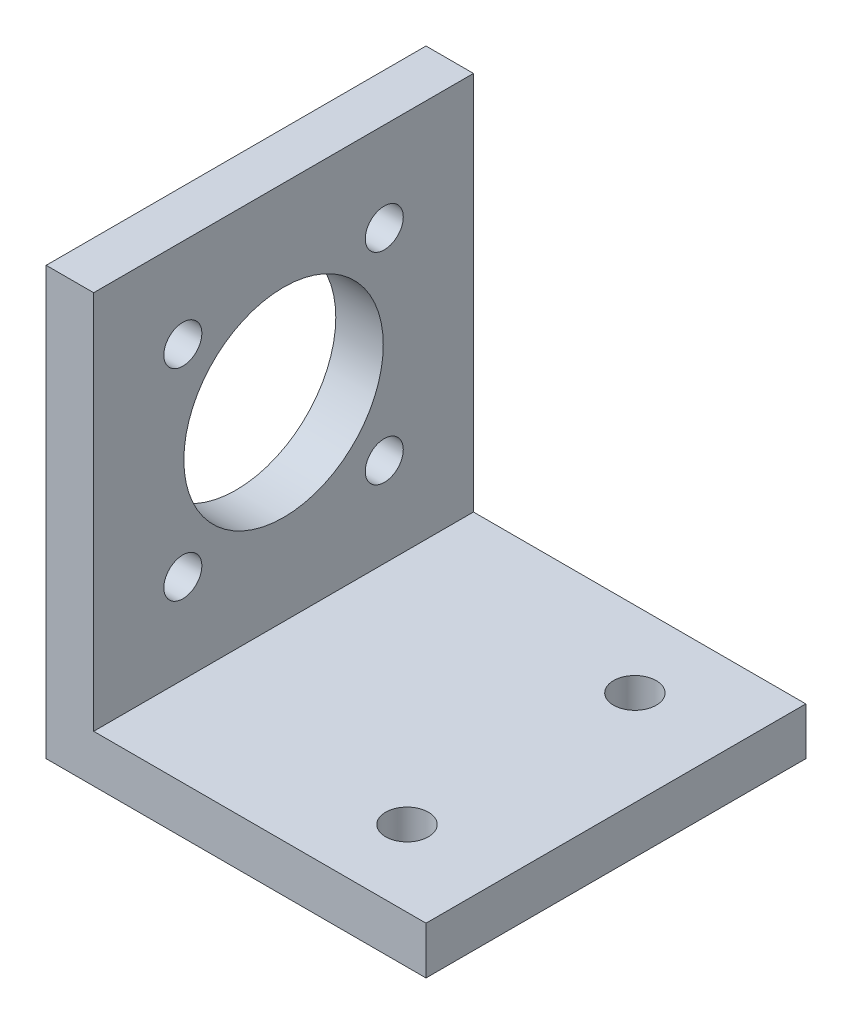
SolidWorks part; units mm, degrees
ref_plane "Front Plane" through (0, 0, 0) normal (0, 0, 1) x (1, 0, 0)
ref_plane "Top Plane" through (0, 0, 0) normal (0, 1, 0) x (1, 0, 0)
ref_plane "Right Plane" through (0, 0, 0) normal (1, 0, 0) x (0, 0, -1)
sketch "Sketch1" plane through (0, 0, 0) normal (0, 1, 0) x (1, 0, 0)
  line L1 (-20, -20) -> (20, -20)
  line L2 (-20, -20) -> (-20, 20)
  line L3 (-20, 20) -> (20, 20)
  line L4 (20, -20) -> (20, 20)
  line L5 (-20, -20) -> (20, 20) construction
  line L6 (-20, 20) -> (20, -20) construction
  point P0 (0, 0)
  dimension "D1" = 40
  dimension "D2" = 40
extrude "Boss-Extrude1" add sketch "Sketch1" along normal blind 5
sketch "Sketch3" plane through (0, 5, 0) normal (0, 1, 0) x (1, 0, 0)
  line L0 (-20, -20) -> (20, -20) construction
  line L1 (-20, 20) -> (-15, 20)
  line L2 (-20, 20) -> (-20, -20)
  line L3 (-20, -20) -> (-15, -20)
  line L4 (-15, 20) -> (-15, -20)
  dimension "D1" = 5
extrude "Boss-Extrude6" add sketch "Sketch3" along normal blind 40
sketch "Sketch4" plane through (0, 5, 0) normal (0, 1, 0) x (1, 0, 0)
  line L0 (20, -20) -> (20, 20) construction
  circle A0 centre (10, 12) radius 2.25
  circle A1 centre (10, -12) radius 2.25
  dimension "D1" = 4.5
  dimension "D2" = 4.5
  dimension "D4" = 10
  dimension "D3" = 10
extrude "Cut-Extrude2" cut sketch "Sketch4" against normal through all
sketch "Sketch5" plane through (-15, 0, 0) normal (1, 0, 0) x (0, 0, -1)
  line L0 (10.6066, 35.6066) -> (10.6066, 14.3934) construction
  line L5 (-20, 5) -> (20, 5) construction
  line L6 (10.6066, 14.3934) -> (-10.6066, 14.3934) construction
  line L7 (20, 45) -> (20, 5) construction
  circle A4 centre (0, 25) radius 10.5
  circle A5 centre (-10.6066, 35.6066) radius 2
  circle A6 centre (10.6066, 35.6066) radius 2
  circle A7 centre (10.6066, 14.3934) radius 2
  circle A8 centre (-10.6066, 14.3934) radius 2
  point P17 (0, 25)
  dimension "D1" = 21
  dimension "D3" = 15
  dimension "D2" = 4
  dimension "D4" = 4
extrude "Cut-Extrude3" cut sketch "Sketch5" against normal through all
